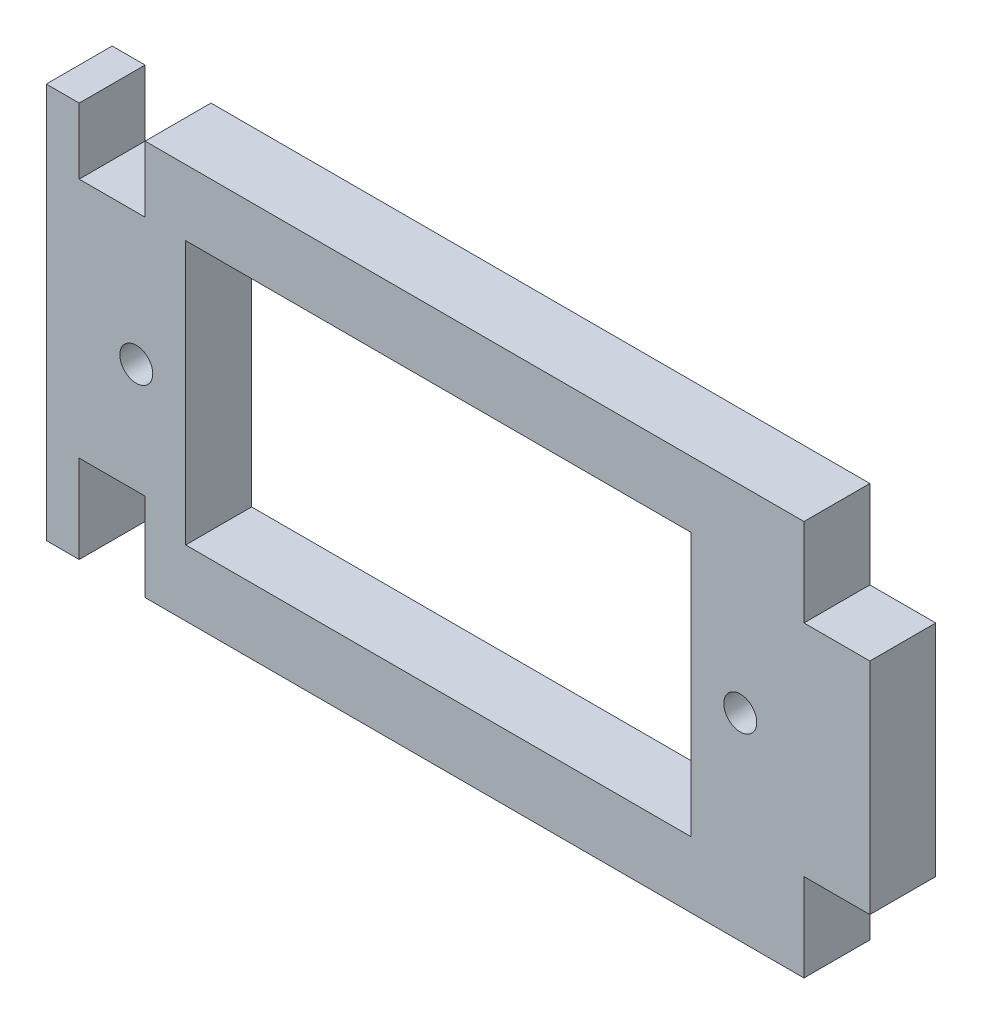
SolidWorks part; units mm, degrees
ref_plane "前视基准面" through (0, 0, 0) normal (0, 0, 1) x (1, 0, 0)
ref_plane "上视基准面" through (0, 0, 0) normal (0, 1, 0) x (1, 0, 0)
ref_plane "右视基准面" through (0, 0, 0) normal (1, 0, 0) x (0, 0, -1)
other "Configuration Table"
sketch "草图1" plane through (0, 0, 0) normal (0, 0, 1) x (1, 0, 0)
  line L16 (0, 0) -> (0, -18)
  line L17 (0, -18) -> (1.5, -18)
  line L18 (1.5, -18) -> (1.5, -14)
  line L19 (1.5, -14) -> (4.5, -14)
  line L20 (4.5, -14) -> (4.5, -18)
  line L23 (0, 0) -> (1.5, 0)
  line L24 (1.5, 0) -> (1.5, -3)
  line L25 (1.5, -3) -> (4.5, -3)
  line L26 (4.5, -3) -> (4.5, 0)
  line L27 (4.5, 0) -> (34.5, 0)
  line L28 (34.5, 0) -> (34.5, -4)
  line L29 (34.5, -4) -> (37.5, -4)
  line L30 (37.5, -4) -> (37.5, -14)
  line L31 (37.5, -14) -> (34.5, -14)
  line L32 (34.5, -14) -> (34.5, -18)
  line L33 (34.5, -18) -> (4.5, -18)
  line L34 (41.6817, -9) -> (-13.0807, -9) construction
  line L35 (4.1, -7.1048) -> (6.35, -7.1048) construction
  line L36 (6.35, -9) -> (6.35, -3)
  line L37 (6.35, -3) -> (29.35, -3)
  line L38 (29.35, -3) -> (29.35, -15)
  line L39 (29.35, -15) -> (6.35, -15)
  line L40 (6.35, -15) -> (6.35, -9)
  circle A0 centre (36, -9) radius 1.5
  circle A1 centre (31.6, -9) radius 0.75
  circle A2 centre (4.1, -9) radius 0.75
  dimension "D12" = 1.5
  dimension "D13" = 1.5
  dimension "D15" = 27.5
  dimension "D11" = 3
  dimension "D1" = 18
  dimension "D2" = 1.5
  dimension "D3" = 4
  dimension "D4" = 3
  dimension "D5" = 3
  dimension "D6" = 30
  dimension "D7" = 4
  dimension "D8" = 3
  dimension "D9" = 10
  dimension "D10" = 4
  dimension "D14" = 4.4
  dimension "D16" = 2.25
  dimension "D17" = 6
  dimension "D18" = 23
  dimension "D19" = 12
extrude "凸台-拉伸9" add sketch "草图1" along normal blind 3 contours L30 A0 L29 L28 L27 L26 L25 L24 L23 L16 L17 L18 L19 L20 L33 L32 L31 A2 A1 L39 L40 L36 L37 L38 | A0
